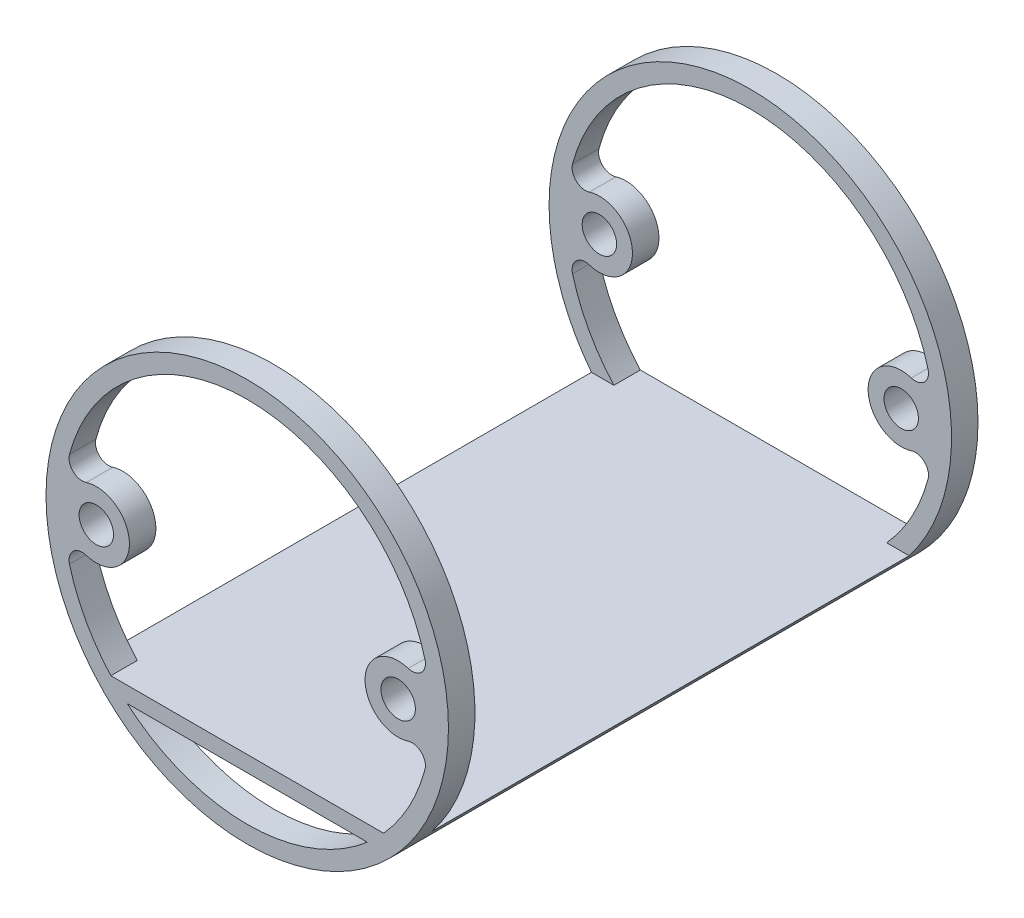
SolidWorks part; units mm, degrees
ref_plane "Front Plane" through (0, 0, 0) normal (0, 0, 1) x (1, 0, 0)
ref_plane "Top Plane" through (0, 0, 0) normal (0, 1, 0) x (1, 0, 0)
ref_plane "Right Plane" through (0, 0, 0) normal (1, 0, 0) x (0, 0, -1)
sketch "Sketch1" plane through (0, 0, 0) normal (0, 0, 1) x (1, 0, 0)
  line L0 (-28.5, 0) -> (28.5, 0) construction
  line L1 (-25.7597, -23.3238) -> (25.7597, -23.3238)
  line L2 (-22.6852, -26.3238) -> (22.6852, -26.3238)
  line L3 (-25.7597, -23.3238) -> (-30, -23.3238) construction
  line L4 (25.7597, -23.3238) -> (30, -23.3238) construction
  circle A0 centre (0, 0) radius 38
  arc A1 (33.5685, 8.9843) -> (-33.5685, 8.9843) centre (0, 0) ccw
  circle A2 centre (-28.5, 0) radius 3.25
  circle A3 centre (28.5, 0) radius 3.25
  arc A4 (-30.3954, -5.9557) -> (-30.3954, 5.9557) centre (-28.5, 0) ccw
  arc A5 (30.3954, 5.9557) -> (30.3954, -5.9557) centre (28.5, 0) ccw
  arc A6 (-33.5685, 8.9843) -> (-30.3954, 5.9557) centre (-31.1535, 8.3379) ccw
  arc A7 (-30.3954, -5.9557) -> (-33.5685, -8.9843) centre (-31.1535, -8.3379) ccw
  arc A8 (30.3954, 5.9557) -> (33.5685, 8.9843) centre (31.1535, 8.3379) ccw
  arc A9 (33.5685, -8.9843) -> (30.3954, -5.9557) centre (31.1535, -8.3379) ccw
  arc A10 (34.75, 0) -> (33.5685, 8.9843) centre (0, 0) ccw construction
  arc A11 (34.75, 0) -> (30.3954, 5.9557) centre (28.5, 0) ccw construction
  arc A12 (30.3954, -5.9557) -> (34.75, 0) centre (28.5, 0) ccw construction
  arc A13 (33.5685, -8.9843) -> (34.75, 0) centre (0, 0) ccw construction
  arc A14 (-33.5685, 8.9843) -> (-34.75, 0) centre (0, 0) ccw construction
  arc A15 (-33.5685, -8.9843) -> (-25.7597, -23.3238) centre (0, 0) ccw
  arc A16 (-30.3954, 5.9557) -> (-34.75, 0) centre (-28.5, 0) ccw construction
  arc A17 (-34.75, 0) -> (-30.3954, -5.9557) centre (-28.5, 0) ccw construction
  arc A18 (-34.75, 0) -> (-33.5685, -8.9843) centre (0, 0) ccw construction
  arc A19 (-25.7597, -23.3238) -> (-22.6852, -26.3238) centre (0, 0) ccw construction
  arc A20 (-22.6852, -26.3238) -> (22.6852, -26.3238) centre (0, 0) ccw
  arc A21 (22.6852, -26.3238) -> (25.7597, -23.3238) centre (0, 0) ccw construction
  arc A22 (25.7597, -23.3238) -> (33.5685, -8.9843) centre (0, 0) ccw
  point P8 (0, 0)
  dimension "D2" = 6.5
  dimension "D3" = 3
  dimension "D4" = 76
  dimension "D5" = 5
  dimension "D1" = 57
  dimension "D6" = 60
  dimension "D7" = 3
extrude "Boss-Extrude1" add sketch "Sketch1" along normal blind 5
sketch "Sketch2" plane through (0, 0, 0) normal (0, 0, -1) x (-1, 0, 0)
  line L0 (-30, -23.3238) -> (30, -23.3238)
  line L1 (27.4054, -26.3238) -> (-27.4054, -26.3238)
  line L2 (-22.6852, -26.3238) -> (22.6852, -26.3238) construction
  line L3 (25.7597, -23.3238) -> (-25.7597, -23.3238) construction
  circle A0 centre (0, 0) radius 38 construction
  arc A1 (-30, -23.3238) -> (-27.4054, -26.3238) centre (0, 0) ccw
  arc A2 (30, -23.3238) -> (-30, -23.3238) centre (0, 0) ccw construction
  arc A3 (-27.4054, -26.3238) -> (27.4054, -26.3238) centre (0, 0) ccw construction
  arc A4 (27.4054, -26.3238) -> (30, -23.3238) centre (0, 0) ccw
extrude "Boss-Extrude2" add sketch "Sketch2" along normal blind 90
sketch "Sketch3" plane through (0, 0, -90) normal (0, 0, -1) x (-1, 0, 0)
  line L0 (-27.4054, -26.3238) -> (27.4054, -26.3238) construction
  line L1 (30, -23.3238) -> (-30, -23.3238) construction
  line L2 (-22.6852, -26.3238) -> (22.6852, -26.3238)
  line L3 (25.7597, -23.3238) -> (-25.7597, -23.3238)
  line L4 (-25.7597, -23.3238) -> (-30, -23.3238) construction
  line L5 (-27.4054, -26.3238) -> (-22.6852, -26.3238) construction
  line L6 (30, -23.3238) -> (25.7597, -23.3238) construction
  line L7 (22.6852, -26.3238) -> (27.4054, -26.3238) construction
  arc A0 (-33.5685, -8.9843) -> (-25.7597, -23.3238) centre (0, 0) ccw construction
  arc A1 (-30.3954, -5.9557) -> (-33.5685, -8.9843) centre (-31.1535, -8.3379) ccw construction
  arc A2 (-30, -23.3238) -> (-27.4054, -26.3238) centre (0, 0) ccw construction
  arc A3 (27.4054, -26.3238) -> (30, -23.3238) centre (0, 0) ccw construction
  arc A4 (30, -23.3238) -> (-30, -23.3238) centre (0, 0) ccw construction
  arc A5 (-27.4054, -26.3238) -> (27.4054, -26.3238) centre (0, 0) ccw construction
  arc A6 (-22.6852, -26.3238) -> (22.6852, -26.3238) centre (0, 0) ccw construction
  arc A7 (25.7597, -23.3238) -> (33.5685, -8.9843) centre (0, 0) ccw construction
  arc A8 (33.5685, -8.9843) -> (30.3954, -5.9557) centre (31.1535, -8.3379) ccw construction
  arc A9 (30.3954, 5.9557) -> (33.5685, 8.9843) centre (31.1535, 8.3379) ccw construction
  circle A10 centre (28.5, 0) radius 3.25 construction
  arc A11 (30.3954, 5.9557) -> (30.3954, -5.9557) centre (28.5, 0) ccw construction
  arc A12 (33.5685, 8.9843) -> (-33.5685, 8.9843) centre (0, 0) ccw construction
  arc A13 (-33.5685, 8.9843) -> (-30.3954, 5.9557) centre (-31.1535, 8.3379) ccw construction
  arc A14 (-30.3954, -5.9557) -> (-30.3954, 5.9557) centre (-28.5, 0) ccw construction
  circle A15 centre (-28.5, 0) radius 3.25 construction
  arc A16 (-33.5685, -8.9843) -> (-25.7597, -23.3238) centre (0, 0) ccw
  arc A17 (-30.3954, -5.9557) -> (-33.5685, -8.9843) centre (-31.1535, -8.3379) ccw
  arc A18 (-30, -23.3238) -> (-27.4054, -26.3238) centre (0, 0) ccw
  arc A19 (27.4054, -26.3238) -> (30, -23.3238) centre (0, 0) ccw
  arc A20 (30, -23.3238) -> (-30, -23.3238) centre (0, 0) ccw
  arc A21 (-27.4054, -26.3238) -> (27.4054, -26.3238) centre (0, 0) ccw
  arc A22 (-22.6852, -26.3238) -> (22.6852, -26.3238) centre (0, 0) ccw
  arc A23 (25.7597, -23.3238) -> (33.5685, -8.9843) centre (0, 0) ccw
  arc A24 (33.5685, -8.9843) -> (30.3954, -5.9557) centre (31.1535, -8.3379) ccw
  arc A25 (30.3954, 5.9557) -> (33.5685, 8.9843) centre (31.1535, 8.3379) ccw
  circle A26 centre (28.5, 0) radius 3.25
  arc A27 (30.3954, 5.9557) -> (30.3954, -5.9557) centre (28.5, 0) ccw
  arc A28 (33.5685, 8.9843) -> (-33.5685, 8.9843) centre (0, 0) ccw
  arc A29 (-33.5685, 8.9843) -> (-30.3954, 5.9557) centre (-31.1535, 8.3379) ccw
  arc A30 (-30.3954, -5.9557) -> (-30.3954, 5.9557) centre (-28.5, 0) ccw
  circle A31 centre (-28.5, 0) radius 3.25
extrude "Boss-Extrude3" add sketch "Sketch3" along normal blind 5
